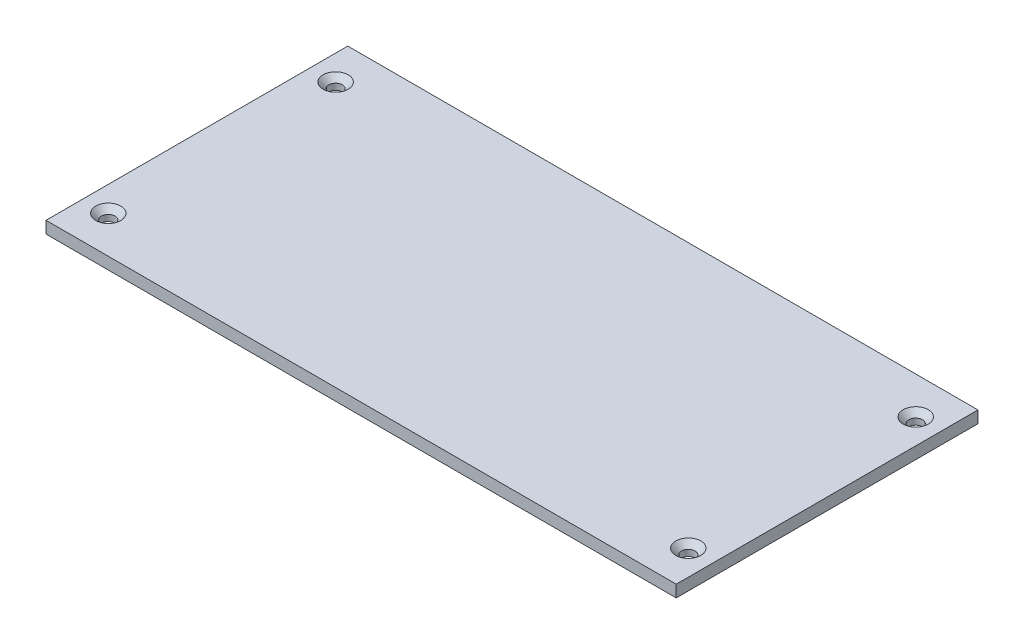
SolidWorks part; units mm, degrees
ref_plane "Front Plane" through (0, 0, 0) normal (0, 0, 1) x (1, 0, 0)
ref_plane "Top Plane" through (0, 0, 0) normal (0, 1, 0) x (1, 0, 0)
ref_plane "Right Plane" through (0, 0, 0) normal (1, 0, 0) x (0, 0, -1)
sketch "Sketch1" plane through (0, 0, 0) normal (0, 1, 0) x (1, 0, 0)
  line L1 (-79.2, -37.925) -> (79.2, -37.925)
  line L2 (-79.2, -37.925) -> (-79.2, 37.925)
  line L3 (-79.2, 37.925) -> (79.2, 37.925)
  line L4 (79.2, -37.925) -> (79.2, 37.925)
  line L5 (-79.2, -37.925) -> (79.2, 37.925) construction
  line L6 (-79.2, 37.925) -> (79.2, -37.925) construction
  point P0 (0, 0)
  dimension "D1" = 75.85
  dimension "D2" = 158.4
extrude "Boss-Extrude1" add sketch "Sketch1" along normal blind 3 contours L2 L3 L4 L1
sketch "Sketch2" plane through (0, 3, 0) normal (0, 1, 0) x (1, 0, 0)
  line L0 (-79.2, 37.925) -> (79.2, 37.925) construction
  line L1 (-79.2, -37.925) -> (-79.2, 37.925) construction
  line L2 (79.2, -37.925) -> (79.2, 37.925) construction
  line L3 (-79.2, -37.925) -> (79.2, -37.925) construction
  point P0 (-72.898, 28.575)
  point P1 (-72.898, -28.575)
  point P2 (72.898, -28.575)
  point P3 (72.898, 28.575)
  dimension "D1" = 9.35
  dimension "D2" = 6.302
  dimension "D3" = 6.302
  dimension "D4" = 9.35
  dimension "D5" = 9.35
  dimension "D6" = 6.302
  dimension "D7" = 6.302
  dimension "D8" = 9.35
hole_wizard "CSK for M3 Countersunk Flat Head Screw1" positions "3DSketch1" profile "Sketch3" countersink size "M3" standard "ISO" end condition up to next
sketch3d "3DSketch1"
  point P0 (-72.898, 3, -28.575)
  point P3 (-72.898, 3, 28.575)
  point P6 (72.898, 3, 28.575)
  point P9 (72.898, 3, -28.575)
sketch "Sketch3" plane through (-72.898, 3, -28.575) normal (1, 0, 0) x (0, 0, 1)
  line L0 (0, 0) -> (0, 3)
  line L1 (0, 3) -> (1.7, 3)
  line L2 (1.7, 3) -> (1.7, 1.45)
  line L3 (1.7, 1.45) -> (3.15, 0)
  line L5 (3.15, 0) -> (0, 0)
  line L6 (-1.7, 1.45) -> (-3.15, 0) construction
  line L11 (0, -6.35) -> (0, 107.95) construction
  dimension "Thru Hole Dia." = 3.4
  dimension "Thru Hole Depth" = 3
  dimension "Near C'Sink Dia." = 6.3
  dimension "Near C'Sink Angle" = 90
